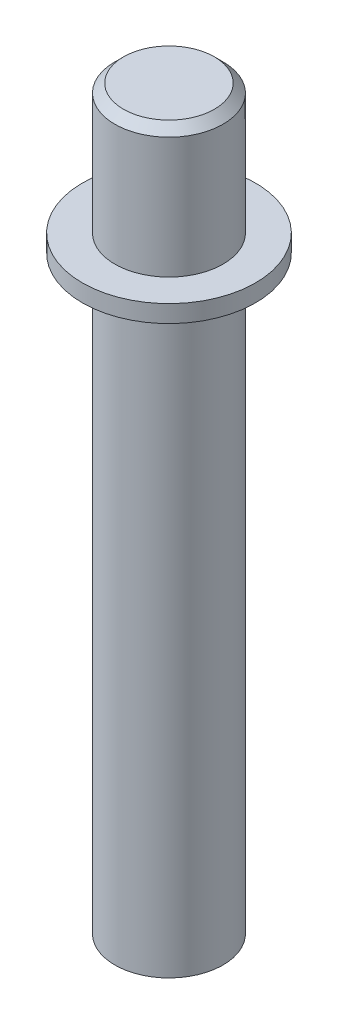
SolidWorks part; units mm, degrees
material "Cast Carbon Steel"
ref_plane "Front Plane" through (0, 0, 0) normal (0, 0, 1) x (1, 0, 0)
ref_plane "Top Plane" through (0, 0, 0) normal (0, 1, 0) x (1, 0, 0)
ref_plane "Right Plane" through (0, 0, 0) normal (1, 0, 0) x (0, 0, -1)
sketch "Sketch1" plane through (0, 0, 0) normal (0, 1, 0) x (1, 0, 0)
  circle A0 centre (0, 0) radius 3.175
  dimension "D1" = 6.35
extrude "Boss-Extrude1" add sketch "Sketch1" along normal blind 14.2875
sketch "Sketch3" plane through (0, 14.2875, 0) normal (0, 1, 0) x (1, 0, 0)
  circle A0 centre (0, 0) radius 5.08
  dimension "D1" = 10.16
extrude "Boss-Extrude2" add sketch "Sketch3" along normal blind 1.016
sketch "Sketch4" plane through (0, 15.3035, 0) normal (0, 1, 0) x (1, 0, 0)
  circle A0 centre (0, 0) radius 3.175
extrude "Boss-Extrude3" add sketch "Sketch4" along normal blind 7.62
chamfer "Chamfer2" distance 0.508 angle 45 1 edges at (0, 22.9235, 3.175)
sketch "Sketch9" plane through (0, 0, 0) normal (0, -1, 0) x (1, 0, 0)
  circle A0 centre (0, 0) radius 3.175
extrude "Boss-Extrude4" add sketch "Sketch9" along normal blind 20.32
